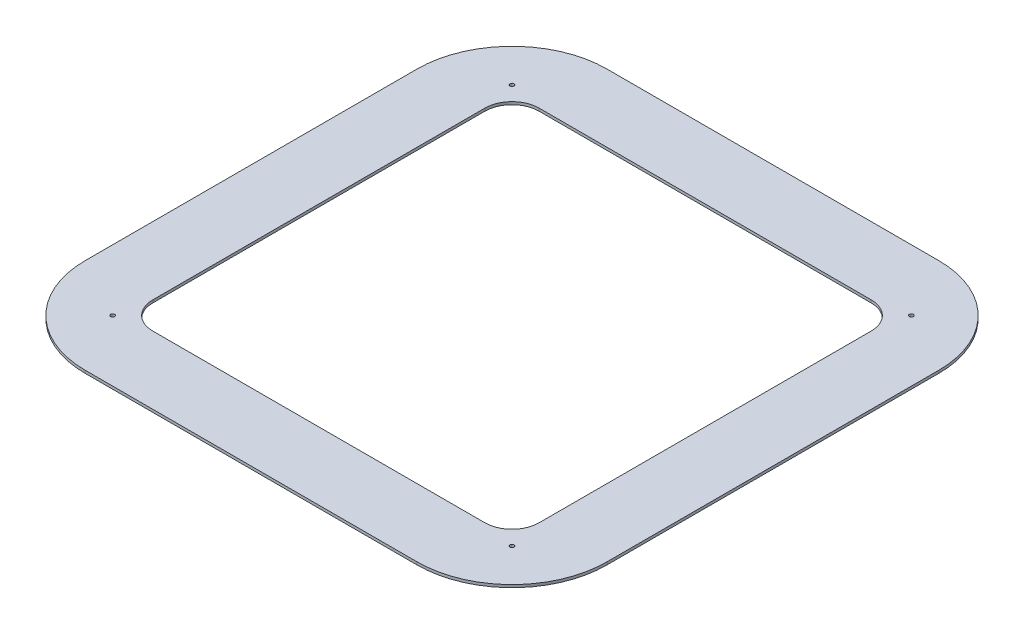
SolidWorks part; units mm, degrees
ref_plane "前视基准面" through (0, 0, 0) normal (0, 0, 1) x (1, 0, 0)
ref_plane "上视基准面" through (0, 0, 0) normal (0, 1, 0) x (1, 0, 0)
ref_plane "右视基准面" through (0, 0, 0) normal (1, 0, 0) x (0, 0, -1)
sketch "草图1" plane through (0, 0, 0) normal (0, 1, 0) x (1, 0, 0)
  line L0 (50, 50) -> (335, 50)
  line L1 (0, 0) -> (385, 0)
  line L2 (0, 0) -> (0, 385)
  line L3 (0, 385) -> (385, 385)
  line L4 (385, 0) -> (385, 385)
  line L5 (335, 50) -> (335, 335)
  line L6 (50, 335) -> (335, 335)
  line L7 (50, 50) -> (50, 335)
  dimension "D1" = 385
  dimension "D2" = 385
  dimension "D3" = 50
extrude "凸台-拉伸1" add sketch "草图1" along normal blind 2
fillet "圆角1" radius 70 4 edges at (0, 1, 0) (385, 1, -385) (0, 1, -385) (385, 1, 0)
fillet "圆角2" radius 20 4 edges at (335, 1, -50) (335, 1, -335) (50, 1, -335) (50, 1, -50)
sketch "草图2" plane through (0, 2, 0) normal (0, 1, 0) x (1, 0, 0)
  line L0 (20.5025, 364.4975) -> (55.8579, 329.1421) construction
  line L1 (192.5, 385) -> (192.5, 335)
  line L3 (315, 335) -> (70, 335) construction
  line L4 (315, 385) -> (70, 385) construction
  line L5 (0, 192.5) -> (50, 192.5)
  line L6 (50, 315) -> (50, 70) construction
  line L7 (0, 315) -> (0, 70) construction
  circle A0 centre (45.1806, 339.8194) radius 1.5
  arc A1 (70, 385) -> (0, 315) centre (70, 315) ccw construction
  arc A2 (70, 335) -> (50, 315) centre (70, 315) ccw construction
  circle A3 centre (339.8194, 339.8194) radius 1.5
  circle A4 centre (45.1806, 45.1806) radius 1.5
  circle A5 centre (339.8194, 45.1806) radius 1.5
  dimension "D1" = 35.1
  dimension "D2" = 3
extrude "切除-拉伸1" cut sketch "草图2" against normal up to next contours A4 | L0 A0 | A0 L0 | A3 | A5
